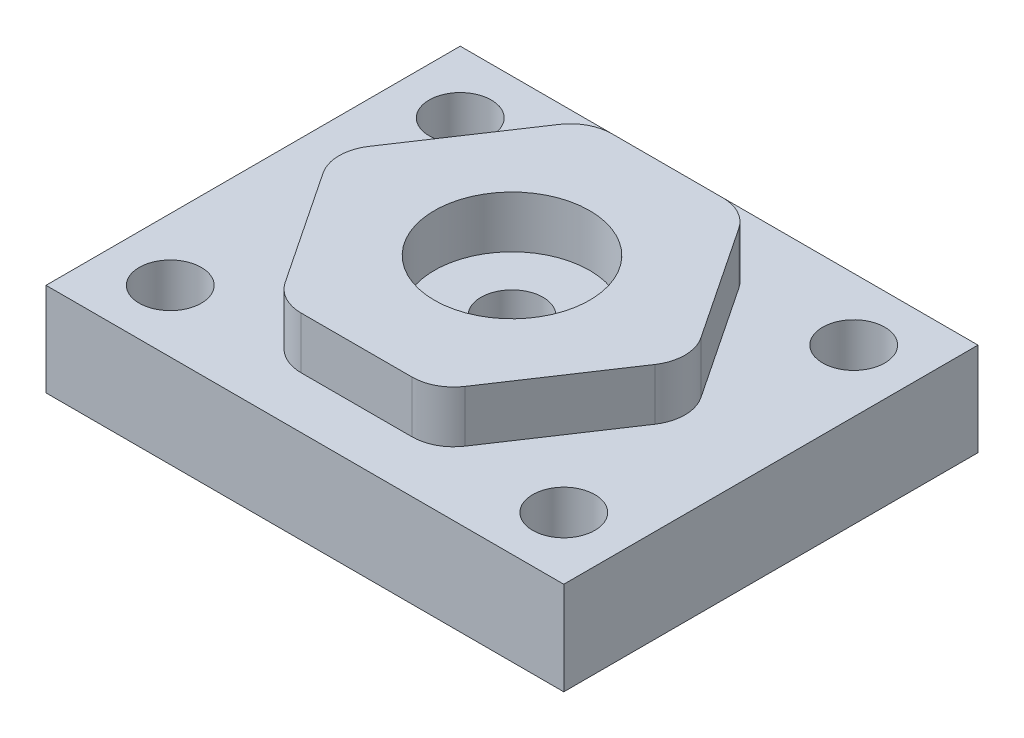
SolidWorks part; units mm, degrees
ref_plane "前视基准面" through (0, 0, 0) normal (0, 0, 1) x (1, 0, 0)
ref_plane "上视基准面" through (0, 0, 0) normal (0, 1, 0) x (1, 0, 0)
ref_plane "右视基准面" through (0, 0, 0) normal (1, 0, 0) x (0, 0, -1)
sketch "草图2" plane through (0, 0, 0) normal (0, 1, 0) x (1, 0, 0)
  line L1 (25, -20) -> (-25, -20)
  line L2 (25, -20) -> (25, 20)
  line L3 (25, 20) -> (-25, 20)
  line L4 (-25, -20) -> (-25, 20)
  line L5 (25, -20) -> (-25, 20) construction
  line L6 (25, 20) -> (-25, -20) construction
  point P0 (0, 0)
  dimension "D1" = 50
  dimension "D2" = 40
extrude "凸台-拉伸1" add sketch "草图2" along normal blind 9
sketch "草图3" plane through (0, 9, 0) normal (0, 1, 0) x (1, 0, 0)
  line L4 (-25, 20) -> (-25, -20)
  line L5 (-25, -20) -> (25, -20)
  line L6 (25, -20) -> (25, 20)
  line L7 (25, 20) -> (-25, 20)
  line L8 (-25, 20) -> (-25, -20)
  line L9 (-25, -20) -> (25, -20)
  line L10 (25, -20) -> (25, 20)
  line L11 (25, 20) -> (-25, 20)
  line L17 (13.5, -15) -> (-13.5, -15)
  line L18 (17.5, -11) -> (17.5, 11)
  line L19 (13.5, 15) -> (-13.5, 15)
  line L20 (-17.5, -11) -> (-17.5, 11)
  line L21 (17.5, -15) -> (-17.5, 15) construction
  line L22 (17.5, 15) -> (-17.5, -15) construction
  arc A0 (-17.5, 11) -> (-13.5, 15) centre (-13.5, 11) cw
  arc A1 (13.5, 15) -> (17.5, 11) centre (13.5, 11) cw
  arc A2 (17.5, -11) -> (13.5, -15) centre (13.5, -11) cw
  arc A3 (-13.5, -15) -> (-17.5, -11) centre (-13.5, -11) cw
  point P2 (0, 0)
  dimension "D4" = 4
  dimension "D5" = 4
  dimension "D2" = 35
  dimension "D3" = 30
  dimension "D1" = 0
extrude "凸台-拉伸3" add sketch "草图3" along normal blind 5 contours L20 A0 L19 A1 L18 A2 L17 A3
sketch "草图6" plane through (0, 14, 0) normal (0, 1, 0) x (1, 0, 0)
  circle A0 centre (0, 0) radius 7.5
  dimension "D1" = 15
extrude "切除-拉伸1" cut sketch "草图6" against normal blind 5
sketch "草图7" plane through (0, 9, 0) normal (0, 1, 0) x (1, 0, 0)
  circle A0 centre (0, 0) radius 3
  dimension "D1" = 6
extrude "切除-拉伸2" cut sketch "草图7" against normal through all
sketch "草图8" plane through (0, 14, 0) normal (0, 1, 0) x (1, 0, 0)
  line L0 (0, 15) -> (0, -15) construction
  line L1 (8.6875, 13.2188) -> (16.0208, 2.2188)
  line L2 (-17.5, 0) -> (17.5, 0) construction
  line L3 (-8.6875, 13.2188) -> (-16.0208, 2.2188)
  line L4 (-13.5, -15) -> (13.5, -15)
  line L5 (17.5, -11) -> (17.5, 11)
  line L6 (13.5, 15) -> (-13.5, 15)
  line L7 (-17.5, 11) -> (-17.5, -11)
  line L8 (-5.3593, -15) -> (5.3593, -15)
  line L9 (17.5, -11) -> (17.5, 11)
  line L10 (5.3593, 15) -> (-5.3593, 15)
  line L11 (-17.5, 11) -> (-17.5, -11)
  line L12 (-8.6875, -13.2188) -> (-16.0208, -2.2188)
  line L13 (8.6875, -13.2188) -> (16.0208, -2.2188)
  arc A0 (16.0208, -2.2188) -> (16.0208, 2.2188) centre (12.6926, 0) ccw
  arc A1 (-16.0208, -2.2188) -> (-16.0208, 2.2188) centre (-12.6926, 0) cw
  arc A2 (-5.3593, -15) -> (-8.6875, -13.2188) centre (-5.3593, -11) cw
  arc A3 (5.3593, -15) -> (8.6875, -13.2188) centre (5.3593, -11) ccw
  arc A4 (-17.5, -11) -> (-13.5, -15) centre (-13.5, -11) ccw
  arc A5 (13.5, -15) -> (17.5, -11) centre (13.5, -11) ccw
  arc A6 (17.5, 11) -> (13.5, 15) centre (13.5, 11) ccw
  arc A7 (-13.5, 15) -> (-17.5, 11) centre (-13.5, 11) ccw
  arc A8 (-17.5, -11) -> (-13.5, -15) centre (-13.5, -11) ccw
  arc A9 (13.5, -15) -> (17.5, -11) centre (13.5, -11) ccw
  arc A10 (17.5, 11) -> (13.5, 15) centre (13.5, 11) ccw
  arc A11 (-13.5, 15) -> (-17.5, 11) centre (-13.5, 11) ccw
  arc A12 (5.3593, 15) -> (8.6875, 13.2188) centre (5.3593, 11) cw
  arc A13 (-5.3593, 15) -> (-8.6875, 13.2188) centre (-5.3593, 11) ccw
  point P24 (17.5, 0)
  point P27 (-17.5, 0)
  point P30 (-7.5, -15)
  point P33 (7.5, -15)
  point P36 (7.5, 15)
  point P39 (-7.5, 15)
  arc M10 (-17.5, -11) -> (-13.5, -15) centre (-13.5, -11) ccw
  line M11 (-13.5, -15) -> (13.5, -15)
  arc M12 (13.5, -15) -> (17.5, -11) centre (13.5, -11) ccw
  line M13 (17.5, -11) -> (17.5, 11)
  arc M14 (17.5, 11) -> (13.5, 15) centre (13.5, 11) ccw
  line M15 (13.5, 15) -> (-13.5, 15)
  arc M16 (-13.5, 15) -> (-17.5, 11) centre (-13.5, 11) ccw
  line M17 (-17.5, 11) -> (-17.5, -11)
  dimension "D2" = 4
  dimension "D4" = 4
  dimension "D3" = 15
  dimension "D1" = 0
extrude "切除-拉伸11" cut sketch "草图8" against normal blind 5 contours A13 A2 L12 A1 L3 M15 M16 M17 M10 M11 | A12 L1 A0 L13 A3 M15 M11 M12 M13 M14
sketch "草图16" plane through (0, 9, 0) normal (0, 1, 0) x (1, 0, 0)
  line L0 (25, 20) -> (-25, 20) construction
  line L1 (-25, 20) -> (-25, -20) construction
  line L2 (0, 20) -> (0, -20) construction
  line L3 (-25, -20) -> (25, -20) construction
  line L4 (-25, 0) -> (25, 0) construction
  line L5 (25, -20) -> (25, 20) construction
  circle A0 centre (-19, 14) radius 3
  circle A1 centre (-19, -14) radius 3
  circle A2 centre (19, -14) radius 3
  circle A3 centre (19, 14) radius 3
  dimension "D1" = 6
  dimension "D2" = 6
  dimension "D3" = 6
extrude "切除-拉伸12" cut sketch "草图16" against normal through all
